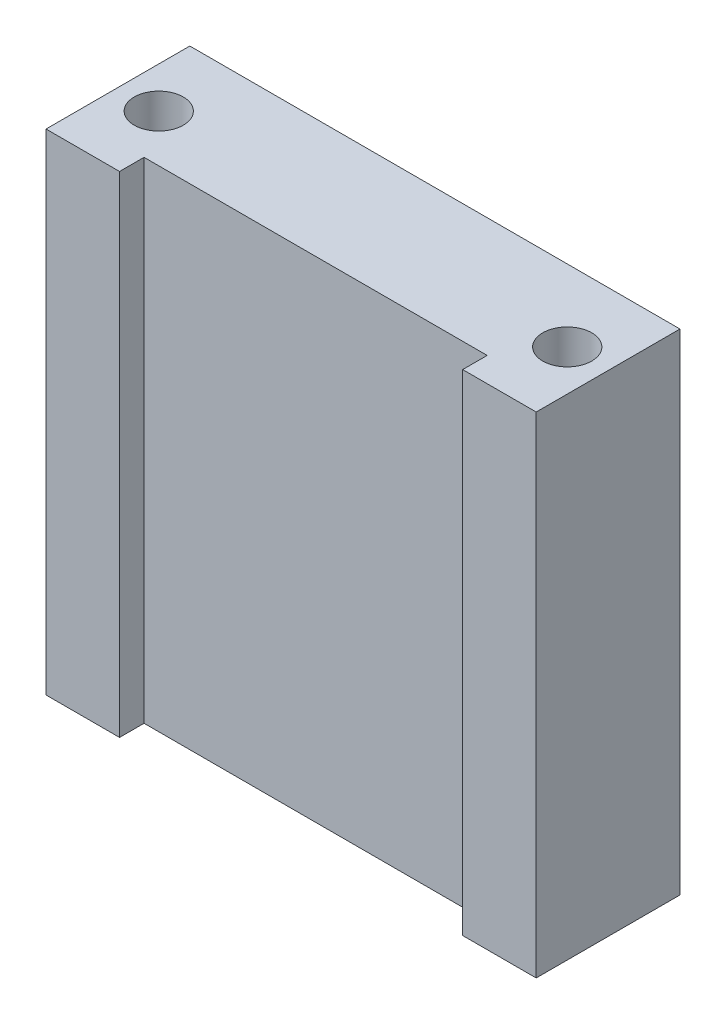
SolidWorks part; units mm, degrees
ref_plane "Alzado" through (0, 0, 0) normal (0, 0, 1) x (1, 0, 0)
ref_plane "Planta" through (0, 0, 0) normal (0, 1, 0) x (1, 0, 0)
ref_plane "Vista lateral" through (0, 0, 0) normal (1, 0, 0) x (0, 0, -1)
sketch "Croquis1" plane through (0, 0, 0) normal (0, 1, 0) x (1, 0, 0)
  line L0 (0, 0) -> (0, 9.2507) construction
  line L2 (-15, -4.4) -> (15, -4.4)
  line L3 (-15, -4.4) -> (-15, 4.4)
  line L4 (-15, 4.4) -> (15, 4.4)
  line L5 (15, -4.4) -> (15, 4.4)
  line L6 (-15, -4.4) -> (15, 4.4) construction
  line L7 (-15, 4.4) -> (15, -4.4) construction
  line L8 (10.5, -5.9) -> (-10.5, -5.9)
  line L9 (10.5, -5.9) -> (10.5, -2.9)
  line L10 (10.5, -2.9) -> (-10.5, -2.9)
  line L11 (-10.5, -5.9) -> (-10.5, -2.9)
  line L12 (10.5, -5.9) -> (-10.5, -2.9) construction
  line L13 (10.5, -2.9) -> (-10.5, -5.9) construction
  circle A0 centre (-12.5, 0) radius 1.5
  circle A2 centre (12.5, 0) radius 1.5
  point P12 (0, -4.4)
  dimension "D1" = 3
  dimension "D4" = 21
  dimension "D2" = 12.5
  dimension "D3" = 30
  dimension "D5" = 3
  dimension "D6" = 8.8
extrude "Saliente-Extruir1" add sketch "Croquis1" along normal blind 30 contours L2 L11 L10 L9 L5 L4 L3 A0 A2
